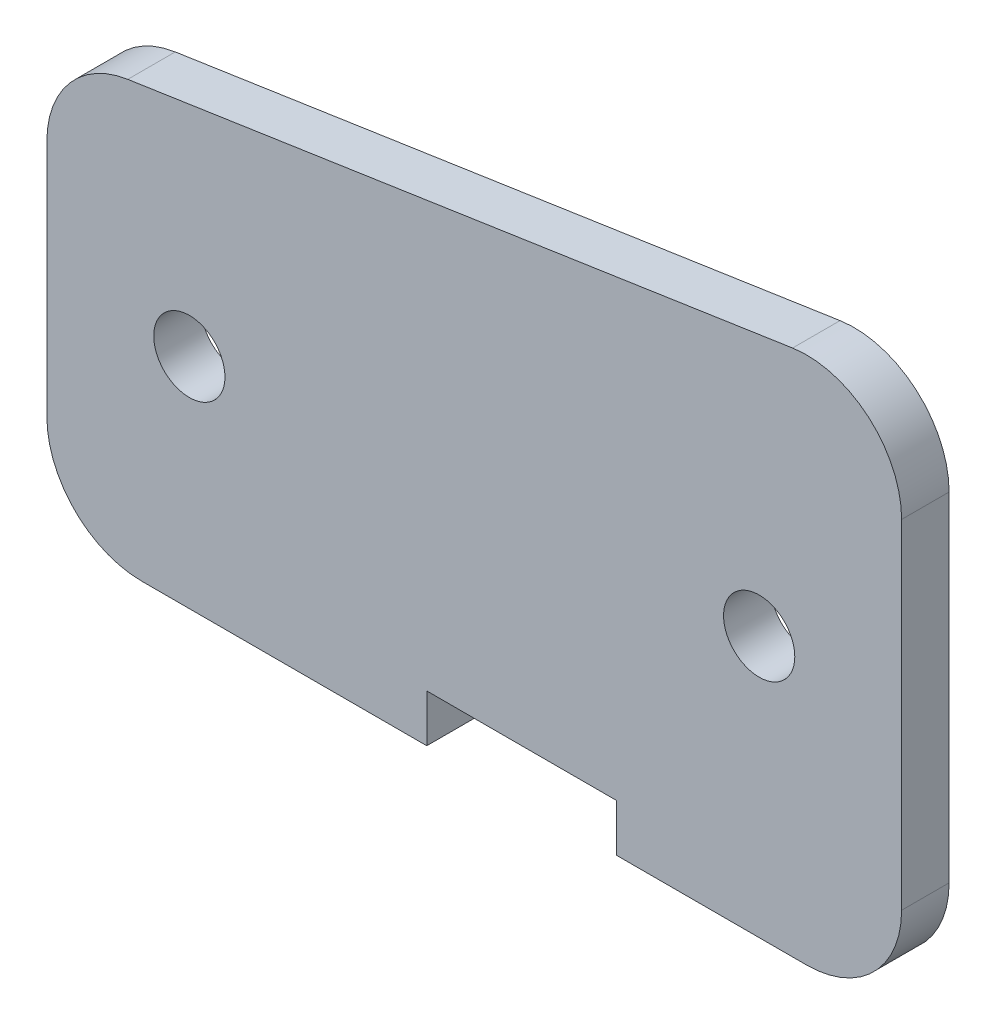
SolidWorks part; units mm, degrees
ref_plane "Front Plane" through (0, 0, 0) normal (0, 0, 1) x (1, 0, 0)
ref_plane "Top Plane" through (0, 0, 0) normal (0, 1, 0) x (1, 0, 0)
ref_plane "Right Plane" through (0, 0, 0) normal (1, 0, 0) x (0, 0, -1)
sketch "Sketch1" plane through (0, 0, 0) normal (0, 0, 1) x (1, 0, 0)
  line L0 (-212.725, 0) -> (-231.775, 0)
  line L8 (-190.5, 0) -> (-190.5, 34.925)
  line L9 (-228.6, 0) -> (-228.6, 29.21)
  line L13 (-180.975, 28.9802) -> (-180.975, 6.35)
  line L14 (-238.125, 22.3127) -> (-238.125, 6.35)
  line L15 (-232.717, 28.5925) -> (-188.267, 35.26)
  line L17 (-212.725, 0) -> (-212.725, 3.175)
  line L18 (-212.725, 3.175) -> (-200.025, 3.175)
  line L19 (-200.025, 0) -> (-200.025, 3.175)
  line L21 (-187.325, 0) -> (-200.025, 0)
  circle A0 centre (-228.6, 14.605) radius 2.3813
  circle A1 centre (-190.5, 17.4625) radius 2.3813
  arc A2 (-238.125, 6.35) -> (-231.775, 0) centre (-231.775, 6.35) ccw
  arc A3 (-180.975, 6.35) -> (-187.325, 0) centre (-187.325, 6.35) cw
  arc A4 (-180.975, 28.9802) -> (-188.267, 35.26) centre (-187.325, 28.9802) ccw
  arc A5 (-238.125, 22.3127) -> (-232.717, 28.5925) centre (-231.775, 22.3127) cw
  dimension "D9" = 4.7625
  dimension "D10" = 4.7625
  dimension "D2" = 6.35
  dimension "D7" = 9.525
  dimension "D8" = 9.525
  dimension "D11" = 12.7
  dimension "D12" = 3.175
  dimension "D13" = 9.525
extrude "Boss-Extrude1" add sketch "Sketch1" along normal blind 3.175 contours A5 L14 A2 L0 L9 A0 L15 | A1 L8 L15 L9 A0 L0 L17 L18 L19 L21 | L13 A4 L15 L8 A1 L21 A3
